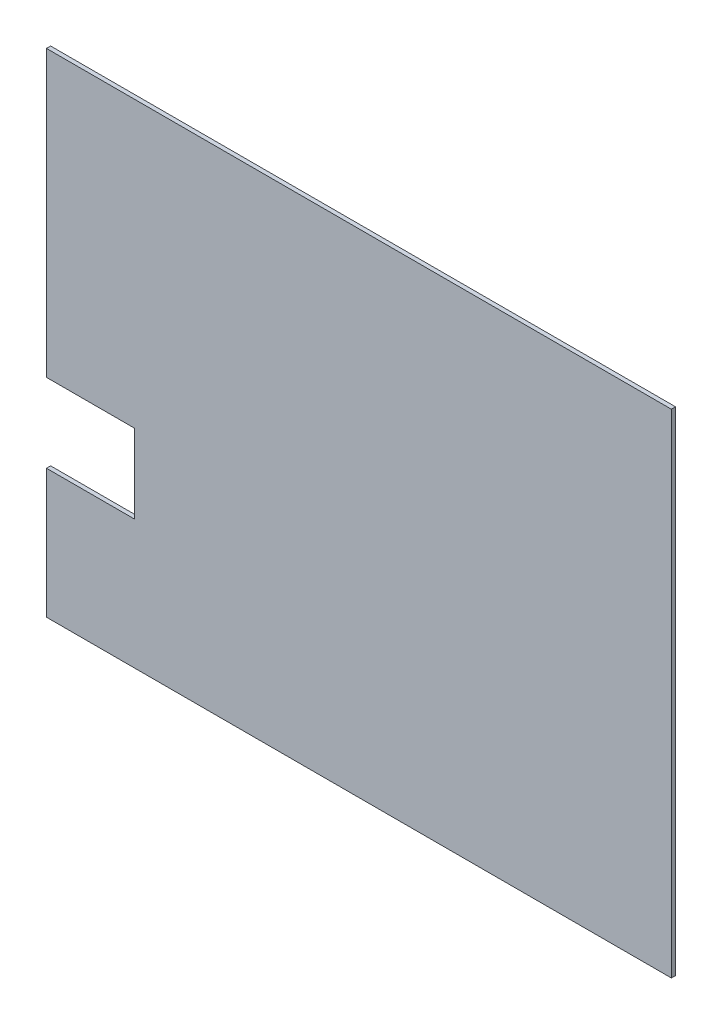
SolidWorks part; units mm, degrees
ref_plane "Front Plane" through (0, 0, 0) normal (0, 0, 1) x (1, 0, 0)
ref_plane "Top Plane" through (0, 0, 0) normal (0, 1, 0) x (1, 0, 0)
ref_plane "Right Plane" through (0, 0, 0) normal (1, 0, 0) x (0, 0, -1)
sketch "Sketch1" plane through (0, 0, 0) normal (0, 0, 1) x (1, 0, 0)
  line L1 (-336.2349, -64.259) -> (-111.1858, -64.259)
  line L2 (-336.2349, -64.259) -> (-336.2349, -241.659)
  line L3 (-336.2349, -241.659) -> (-111.1858, -241.659)
  line L4 (-111.1858, -64.259) -> (-111.1858, -241.659)
extrude "Boss-Extrude1" add sketch "Sketch1" along normal blind 1.5
sketch "Sketch2" plane through (0, 0, 0) normal (0, 0, -1) x (-1, 0, 0)
  line L1 (304.5212, -166.8599) -> (342.2335, -166.8599)
  line L2 (304.5212, -166.8599) -> (304.5212, -195.1963)
  line L3 (304.5212, -195.1963) -> (342.2335, -195.1963)
  line L4 (342.2335, -166.8599) -> (342.2335, -195.1963)
extrude "Cut-Extrude1" cut sketch "Sketch2" against normal through all both
